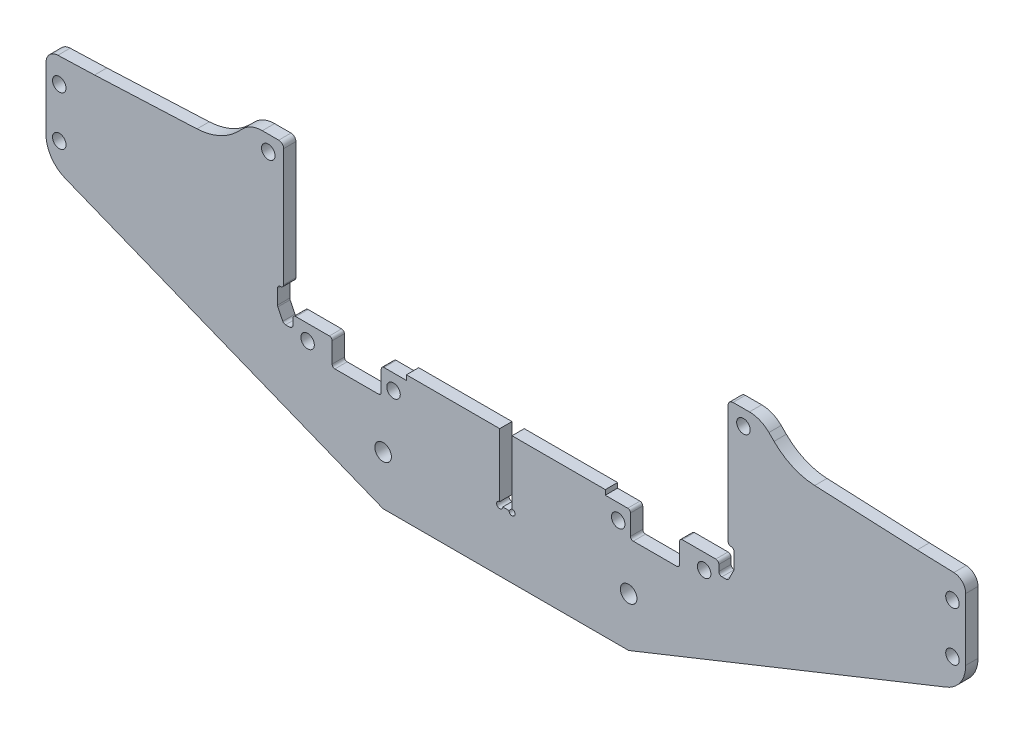
SolidWorks part; units mm, degrees
ref_plane "前视基准面" through (0, 0, 0) normal (0, 0, 1) x (1, 0, 0)
ref_plane "上视基准面" through (0, 0, 0) normal (0, 1, 0) x (1, 0, 0)
ref_plane "右视基准面" through (0, 0, 0) normal (1, 0, 0) x (0, 0, -1)
sketch "草图1" plane through (0, 0, 0) normal (0, 0, 1) x (1, 0, 0)
  line L0 (36.2, 20.95) -> (36.2, 1.75)
  line L1 (37.2, 0.75) -> (37.2, -1.632)
  line L2 (37.1472, -1.8556) -> (36.3382, -3.4736)
  line L3 (35.891, -3.75) -> (35.2, -3.75)
  line L4 (34.7, -3.25) -> (34.7, -2.25)
  line L5 (34.2, -1.75) -> (28.75, -1.75)
  line L6 (28.3, -2.2) -> (28.3, -5.5)
  line L7 (27.85, -5.95) -> (20.75, -5.95)
  line L8 (20.3, -5.5) -> (20.3, -2.2)
  line L9 (19.85, -1.75) -> (16.2, -1.75)
  line L10 (16.2, -1.75) -> (16.2, -0.95)
  line L11 (16.2, -0.95) -> (1, -0.95)
  line L12 (1, -0.95) -> (1, -11.25)
  line L13 (0.5, -11.75) -> (-0.5, -11.75)
  line L14 (-1, -11.25) -> (-1, -0.95)
  line L15 (-1, -0.95) -> (-16.2, -0.95)
  line L16 (-16.2, -0.95) -> (-16.2, -1.75)
  line L17 (-16.2, -1.75) -> (-19.85, -1.75)
  line L18 (-20.3, -2.2) -> (-20.3, -5.5)
  line L19 (-20.75, -5.95) -> (-27.85, -5.95)
  line L20 (-28.3, -5.5) -> (-28.3, -2.2)
  line L21 (-28.75, -1.75) -> (-34.2, -1.75)
  line L22 (-34.7, -2.25) -> (-34.7, -3.25)
  line L23 (-35.2, -3.75) -> (-35.891, -3.75)
  line L24 (-36.3382, -3.4736) -> (-37.1472, -1.8556)
  line L25 (-37.2, -1.632) -> (-37.2, 0.75)
  line L26 (-36.2, 1.75) -> (-36.2, 20.95)
  line L27 (-37, 21.75) -> (-39.6716, 21.75)
  line L28 (-42.8536, 20.432) -> (-43.686, 19.5996)
  line L29 (-50.313, 16.6805) -> (-67, 15.9389)
  line L30 (-67, 15.9389) -> (-72.9788, 15.7396)
  line L31 (-74.9122, 13.7407) -> (-74.9122, 3.6)
  line L32 (-71.7691, -1.0424) -> (-20, -21.75)
  line L33 (-20, -21.75) -> (20, -21.75)
  line L34 (20, -21.75) -> (71.7691, -1.0424)
  line L35 (74.9122, 3.6) -> (74.9122, 13.7407)
  line L36 (72.9788, 15.7396) -> (67, 15.9389)
  line L37 (67, 15.9389) -> (50.313, 16.6805)
  line L38 (43.686, 19.5996) -> (42.8536, 20.432)
  line L39 (39.6716, 21.75) -> (37, 21.75)
  circle A0 centre (72.75, 3.7572) radius 1.1
  circle A1 centre (72.75, 11.7572) radius 1.1
  circle A2 centre (38.7, 19.25) radius 1.1
  circle A3 centre (32.3, -4.25) radius 1.1
  circle A4 centre (18.3, -4.25) radius 1.1
  circle A5 centre (20, -13.75) radius 1.35
  circle A6 centre (-18.3, -4.25) radius 1.1
  circle A7 centre (-32.3, -4.25) radius 1.1
  circle A8 centre (-20, -13.75) radius 1.35
  circle A9 centre (-38.7, 19.25) radius 1.1
  circle A10 centre (-72.75, 3.7572) radius 1.1
  circle A11 centre (-72.75, 11.7572) radius 1.1
  arc A12 (36.2, 1.75) -> (36.7, 1.25) centre (36.7, 1.75) ccw
  arc A13 (37.2, 0.75) -> (36.7, 1.25) centre (36.7, 0.75) ccw
  arc A14 (37.1472, -1.8556) -> (37.2, -1.632) centre (36.7, -1.632) ccw
  arc A15 (35.891, -3.75) -> (36.3382, -3.4736) centre (35.891, -3.25) ccw
  arc A16 (34.7, -3.25) -> (35.2, -3.75) centre (35.2, -3.25) ccw
  arc A17 (34.7, -2.25) -> (34.2, -1.75) centre (34.2, -2.25) ccw
  arc A18 (28.75, -1.75) -> (28.3, -2.2) centre (28.75, -2.2) ccw
  arc A19 (27.85, -5.95) -> (28.3, -5.5) centre (27.85, -5.5) ccw
  arc A20 (20.3, -5.5) -> (20.75, -5.95) centre (20.75, -5.5) ccw
  arc A21 (20.3, -2.2) -> (19.85, -1.75) centre (19.85, -2.2) ccw
  arc A22 (0.5, -11.75) -> (1, -11.25) centre (1, -11.75) ccw
  arc A23 (-1, -11.25) -> (-0.5, -11.75) centre (-1, -11.75) ccw
  arc A24 (-19.85, -1.75) -> (-20.3, -2.2) centre (-19.85, -2.2) ccw
  arc A25 (-20.75, -5.95) -> (-20.3, -5.5) centre (-20.75, -5.5) ccw
  arc A26 (-28.3, -5.5) -> (-27.85, -5.95) centre (-27.85, -5.5) ccw
  arc A27 (-28.3, -2.2) -> (-28.75, -1.75) centre (-28.75, -2.2) ccw
  arc A28 (-34.2, -1.75) -> (-34.7, -2.25) centre (-34.2, -2.25) ccw
  arc A29 (-35.2, -3.75) -> (-34.7, -3.25) centre (-35.2, -3.25) ccw
  arc A30 (-36.3382, -3.4736) -> (-35.891, -3.75) centre (-35.891, -3.25) ccw
  arc A31 (-37.2, -1.632) -> (-37.1472, -1.8556) centre (-36.7, -1.632) ccw
  arc A32 (-36.7, 1.25) -> (-37.2, 0.75) centre (-36.7, 0.75) ccw
  arc A33 (-36.7, 1.25) -> (-36.2, 1.75) centre (-36.7, 1.75) ccw
  arc A34 (-36.2, 20.95) -> (-37, 21.75) centre (-37, 20.95) ccw
  arc A35 (-39.6716, 21.75) -> (-42.8536, 20.432) centre (-39.6716, 17.25) ccw
  arc A36 (-50.313, 16.6805) -> (-43.686, 19.5996) centre (-50.757, 26.6707) ccw
  arc A37 (-72.9788, 15.7396) -> (-74.9122, 13.7407) centre (-72.9122, 13.7407) ccw
  arc A38 (-74.9122, 3.6) -> (-71.7691, -1.0424) centre (-69.9122, 3.6) ccw
  arc A39 (71.7691, -1.0424) -> (74.9122, 3.6) centre (69.9122, 3.6) ccw
  arc A40 (74.9122, 13.7407) -> (72.9788, 15.7396) centre (72.9122, 13.7407) ccw
  arc A41 (43.686, 19.5996) -> (50.313, 16.6805) centre (50.757, 26.6707) ccw
  arc A42 (42.8536, 20.432) -> (39.6716, 21.75) centre (39.6716, 17.25) ccw
  arc A43 (37, 21.75) -> (36.2, 20.95) centre (37, 20.95) ccw
extrude "凸台-拉伸1" add sketch "草图1" along normal blind 2
